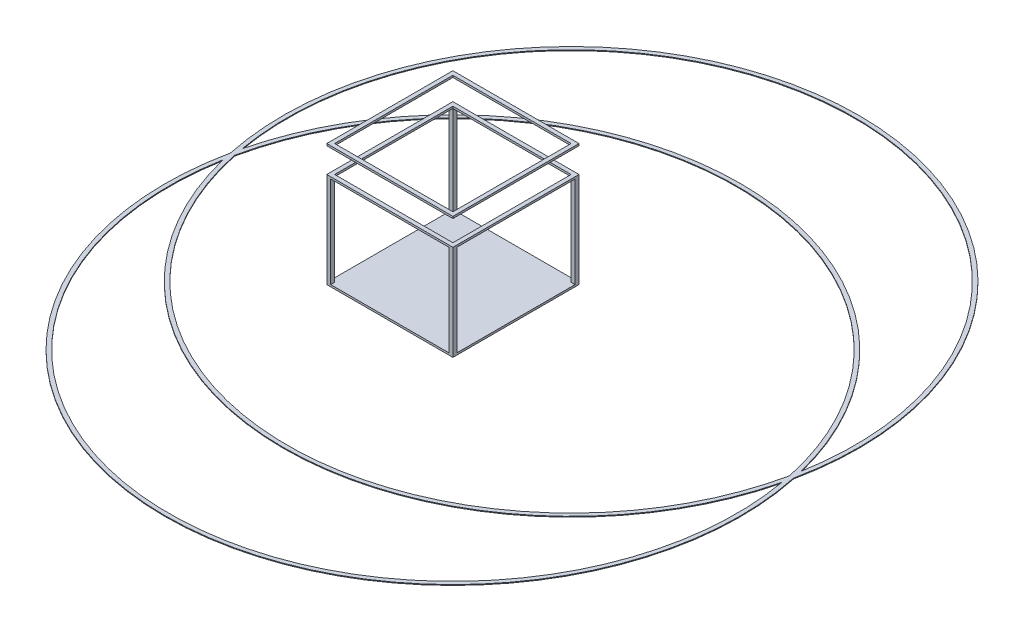
SolidWorks part; units mm, degrees
ref_plane "Front Plane" through (0, 0, 0) normal (0, 0, 1) x (1, 0, 0)
ref_plane "Top Plane" through (0, 0, 0) normal (0, 1, 0) x (1, 0, 0)
ref_plane "Right Plane" through (0, 0, 0) normal (1, 0, 0) x (0, 0, -1)
sketch "Sketch1" plane through (0, 0, 0) normal (0, 1, 0) x (1, 0, 0)
  line L1 (-203.2, -203.2) -> (203.2, -203.2)
  line L2 (-203.2, -203.2) -> (-203.2, 203.2)
  line L3 (-203.2, 203.2) -> (203.2, 203.2)
  line L4 (203.2, -203.2) -> (203.2, 203.2)
  line L5 (-203.2, -203.2) -> (203.2, 203.2) construction
  line L6 (-203.2, 203.2) -> (203.2, -203.2) construction
  point P0 (0, 0)
  dimension "D1" = 406.4
  dimension "D2" = 406.4
extrude "Boss-Extrude1" add sketch "Sketch1" along normal blind 6.35
sketch "Sketch2" plane through (0, 6.35, 0) normal (0, 1, 0) x (1, 0, 0)
  line L0 (0, 203.2) -> (0, -203.2) construction
  line L1 (-203.2, -203.2) -> (-190.5, -203.2)
  line L2 (-203.2, -203.2) -> (-203.2, -190.5)
  line L3 (-203.2, -190.5) -> (-190.5, -190.5)
  line L4 (-190.5, -203.2) -> (-190.5, -190.5)
  line L5 (203.2, 203.2) -> (-203.2, 203.2) construction
  line L6 (-203.2, -203.2) -> (203.2, -203.2) construction
  line L7 (-203.2, 0) -> (203.2, 0) construction
  line L8 (-203.2, 203.2) -> (-203.2, -203.2) construction
  line L9 (203.2, -203.2) -> (203.2, 203.2) construction
  line L10 (190.5, -203.2) -> (190.5, -190.5)
  line L11 (203.2, -190.5) -> (190.5, -190.5)
  line L12 (203.2, -203.2) -> (203.2, -190.5)
  line L13 (203.2, -203.2) -> (190.5, -203.2)
  line L14 (-190.5, 203.2) -> (-190.5, 190.5)
  line L15 (-203.2, 190.5) -> (-190.5, 190.5)
  line L16 (-203.2, 203.2) -> (-203.2, 190.5)
  line L17 (-203.2, 203.2) -> (-190.5, 203.2)
  line L18 (203.2, 203.2) -> (190.5, 203.2)
  line L19 (203.2, 203.2) -> (203.2, 190.5)
  line L20 (203.2, 190.5) -> (190.5, 190.5)
  line L21 (190.5, 203.2) -> (190.5, 190.5)
  dimension "D1" = 381
extrude "Boss-Extrude2" add sketch "Sketch2" along normal blind 294.64
sketch "Sketch3" plane through (0, 300.99, 0) normal (0, 1, 0) x (1, 0, 0)
  line L1 (203.2, 203.2) -> (-203.2, 203.2)
  line L2 (203.2, 203.2) -> (203.2, -203.2)
  line L3 (203.2, -203.2) -> (-203.2, -203.2)
  line L4 (-203.2, 203.2) -> (-203.2, -203.2)
  line L5 (203.2, 203.2) -> (-203.2, -203.2) construction
  line L6 (203.2, -203.2) -> (-203.2, 203.2) construction
  line L7 (190.5, 190.5) -> (-190.5, 190.5)
  line L8 (190.5, 190.5) -> (190.5, -190.5)
  line L9 (190.5, -190.5) -> (-190.5, -190.5)
  line L10 (-190.5, 190.5) -> (-190.5, -190.5)
  line L11 (190.5, 190.5) -> (-190.5, -190.5) construction
  line L12 (190.5, -190.5) -> (-190.5, 190.5) construction
  point P0 (0, 0)
  point P5 (0, 0)
extrude "Boss-Extrude3" add sketch "Sketch3" along normal blind 6.35
ref_plane "Plane1" through (0, 387.35, 0) normal (0, 1, 0) x (1, 0, 0)
sketch "Sketch5" plane through (0, 387.35, 0) normal (0, 1, 0) x (1, 0, 0)
  line L1 (-203.2, -203.2) -> (203.2, -203.2)
  line L2 (-203.2, -203.2) -> (-203.2, 203.2)
  line L3 (-203.2, 203.2) -> (203.2, 203.2)
  line L4 (203.2, -203.2) -> (203.2, 203.2)
  line L5 (-190.5, -190.5) -> (190.5, -190.5)
  line L6 (-190.5, -190.5) -> (-190.5, 190.5)
  line L7 (-190.5, 190.5) -> (190.5, 190.5)
  line L8 (190.5, -190.5) -> (190.5, 190.5)
extrude "Boss-Extrude4" add sketch "Sketch5" along normal blind 6.35 separate body
sketch "Sketch6" plane through (203.2, 0, 0) normal (1, 0, 0) x (0, 0, -1)
  line L0 (0, 49.53) -> (0, 6.35) construction
  line L1 (-190.5, 6.35) -> (190.5, 6.35) construction
  line L2 (-30.48, 6.35) -> (30.48, 6.35)
  line L3 (30.48, 6.35) -> (30.48, 49.53)
  line L4 (-30.48, 49.53) -> (-30.48, 6.35)
  arc A0 (30.48, 49.53) -> (-30.48, 49.53) centre (0, 49.53) ccw
  point P8 (0, 6.35)
  point P10 (0, 80.01)
  dimension "D2" = 60.96
  dimension "D1" = 73.66
extrude "Boss-Extrude5" [suppressed] add sketch "Sketch6" against normal up to surface (406.4 mm away)
sketch "Sketch7" plane through (0, 0, 203.2) normal (0, 0, 1) x (1, 0, 0)
  line L0 (-215.9, 49.53) -> (-215.9, 6.35) construction
  line L1 (-246.38, 6.35) -> (-185.42, 6.35)
  line L2 (-185.42, 6.35) -> (-185.42, 49.53)
  line L3 (-246.38, 49.53) -> (-246.38, 6.35)
  line L5 (-190.5, 6.35) -> (190.5, 6.35) construction
  arc A0 (-185.42, 49.53) -> (-246.38, 49.53) centre (-215.9, 49.53) ccw
  point P5 (-215.9, 6.35)
  point P7 (-215.9, 80.01)
  dimension "D2" = 60.96
  dimension "D1" = 73.66
  dimension "D3" = 185.42
extrude "Boss-Extrude6" [suppressed] add sketch "Sketch7" against normal up to surface (406.4 mm away)
sketch "Sketch8" plane through (0, 6.35, 0) normal (0, 1, 0) x (1, 0, 0)
  circle A0 centre (190.5, -190.5) radius 914.4
  circle A1 centre (190.5, 190.5) radius 914.4
  circle A2 centre (190.5, 190.5) radius 927.1
  circle A3 centre (190.5, -190.5) radius 927.1
  dimension "D1" = 1828.8
  dimension "D2" = 12.7
extrude "Boss-Extrude8" add sketch "Sketch8" along normal blind 2.54 separate body contours A1 A3 A2 A0 | A3 A2 A1 | A2 A3 A0 | A2 A3 A1 A0 | A1 A3 A0 | A0 A2 A1
sketch "Sketch9" [suppressed] plane through (0, 6.35, 0) normal (0, 1, 0) x (1, 0, 0)
  circle A0 centre (228.6, 0) radius 30.226
  dimension "D1" = 60.452
  dimension "D2" = 228.6
extrude "Boss-Extrude9" [suppressed] add sketch "Sketch9" along normal blind 914.4 separate body
ref_plane "Plane2" [suppressed] through (0, 774.7, 0) normal (0, -1, 0) x (-1, 0, 0)
sketch "Sketch10" [suppressed] plane through (0, 774.7, 0) normal (0, -1, 0) x (-1, 0, 0)
  circle A0 centre (-228.6, 0) radius 31.75
  dimension "D1" = 63.5
extrude "Boss-Extrude10" [suppressed] add sketch "Sketch10" along normal offset from surface (34.29 mm away) 734.06
ref_plane "Plane3" [suppressed] through (0, 152.4, 0) normal (0, 1, 0) x (1, 0, 0)
sketch "Sketch12" [suppressed] plane through (0, 152.4, 0) normal (0, 1, 0) x (1, 0, 0)
  line L1 (-203.2, 203.2) -> (203.2, 203.2)
  line L2 (-203.2, 203.2) -> (-203.2, -203.2)
  line L3 (-203.2, -203.2) -> (203.2, -203.2)
  line L4 (203.2, 203.2) -> (203.2, -203.2)
  line L5 (-190.5, 190.5) -> (190.5, 190.5)
  line L6 (-190.5, 190.5) -> (-190.5, -190.5)
  line L7 (-190.5, -190.5) -> (190.5, -190.5)
  line L8 (190.5, 190.5) -> (190.5, -190.5)
extrude "Boss-Extrude11" [suppressed] add sketch "Sketch12" along normal blind 20.32
